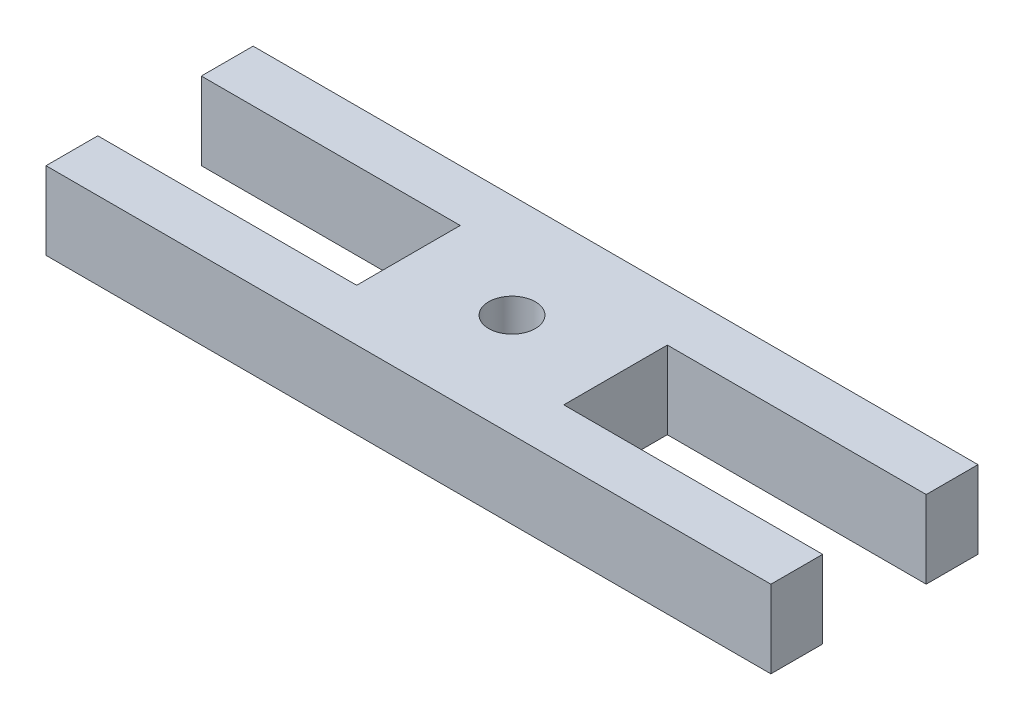
SolidWorks part; units mm, degrees
ref_plane "Front Plane" through (0, 0, 0) normal (0, 0, 1) x (1, 0, 0)
ref_plane "Top Plane" through (0, 0, 0) normal (0, 1, 0) x (1, 0, 0)
ref_plane "Right Plane" through (0, 0, 0) normal (1, 0, 0) x (0, 0, -1)
sketch "Sketch1" plane through (0, 0, 0) normal (0, 1, 0) x (1, 0, 0)
  line L12 (-27.5831, 22.4062) -> (-27.5831, 24.4062)
  line L25 (-20.5831, 25.4062) -> (-20.5831, 26.4062)
  line L26 (-20.5831, 25.4062) -> (-25.5831, 25.4062)
  line L27 (-25.5831, 25.4062) -> (-25.5831, 23.4062)
  line L28 (-25.5831, 23.4062) -> (-20.5831, 23.4062)
  line L29 (-20.5831, 23.4062) -> (-20.5831, 22.4062)
  line L30 (-20.5831, 22.4062) -> (-25.5831, 22.4062)
  line L31 (-20.5831, 26.4062) -> (-29.5308, 26.4062)
  line L32 (-25.5831, 22.4062) -> (-29.5831, 22.4062)
  line L33 (-20.5831, 26.4062) -> (-34.5831, 26.4062)
  line L34 (-20.5831, 22.4062) -> (-34.5831, 22.4062)
  line L35 (-34.5831, 22.4062) -> (-34.5831, 23.4062)
  line L36 (-34.5831, 23.4062) -> (-29.5831, 23.4062)
  line L37 (-29.5831, 23.4062) -> (-29.5831, 25.4062)
  line L38 (-29.5831, 25.4062) -> (-34.5831, 25.4062)
  line L39 (-34.5831, 25.4062) -> (-34.5831, 26.4062)
  circle A1 centre (-27.5831, 24.4062) radius 0.45
extrude "Boss-Extrude3" add sketch "Sketch1" along normal blind 1.5
